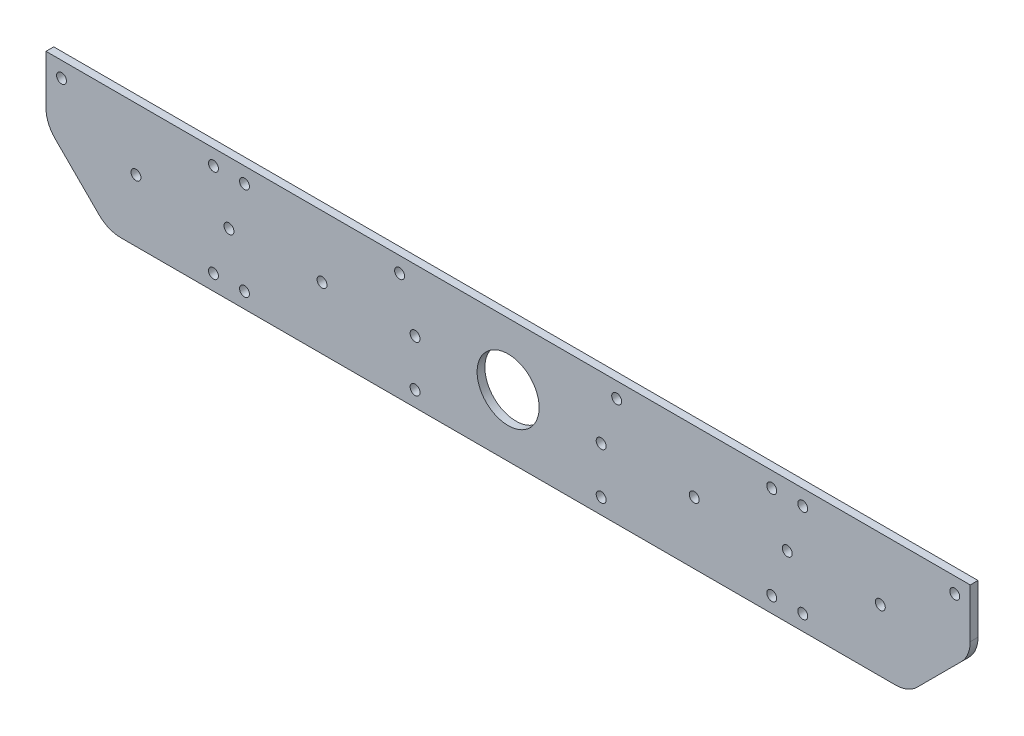
SolidWorks part; units mm, degrees
ref_plane "Front Plane" through (0, 0, 0) normal (0, 0, 1) x (1, 0, 0)
ref_plane "Top Plane" through (0, 0, 0) normal (0, 1, 0) x (1, 0, 0)
ref_plane "Right Plane" through (0, 0, 0) normal (1, 0, 0) x (0, 0, -1)
sketch "Sketch1" plane through (0, 0, 0) normal (0, 0, 1) x (1, 0, 0)
  line L0 (-189.23, 0) -> (189.23, 0) construction
  line L1 (-189.23, -25.4) -> (189.23, -25.4)
  line L2 (-189.23, -25.4) -> (-189.23, 25.4)
  line L3 (-189.23, 25.4) -> (189.23, 25.4)
  line L4 (189.23, -25.4) -> (189.23, 25.4)
  line L5 (0, 25.4) -> (0, -25.4) construction
  circle A0 centre (0, 0) radius 2.032
  circle A9 centre (-38.1, 0) radius 2.032
  circle A10 centre (-76.2, 0) radius 2.032
  circle A11 centre (-114.3, 0) radius 2.032
  circle A12 centre (-152.4, 0) radius 2.032
  circle A13 centre (76.2, 0) radius 2.032
  circle A14 centre (114.3, 0) radius 2.032
  circle A15 centre (152.4, 0) radius 2.032
  circle A16 centre (38.1, 0) radius 2.032
  dimension "D3" = 4.064
  dimension "D5" = 5
  dimension "D1" = 50.8
  dimension "D2" = 378.46
  dimension "D4" = 25.4
  dimension "D6" = 38.1
extrude "Boss-Extrude1" add sketch "Sketch1" along normal blind 3.175
sketch "Sketch2" plane through (0, 0, 3.175) normal (0, 0, 1) x (1, 0, 0)
  circle A0 centre (0, 0) radius 12.7
  dimension "D1" = 25.4
extrude "Cut-Extrude1" cut sketch "Sketch2" against normal through all
sketch "Sketch3" plane through (0, 0, 3.175) normal (0, 0, 1) x (1, 0, 0)
  circle A0 centre (-38.1, -19.05) radius 2.032
  circle A1 centre (-44.45, 19.05) radius 2.032
  circle A2 centre (44.45, 19.05) radius 2.032
  circle A3 centre (38.1, -19.05) radius 2.032
  dimension "D1" = 4.064
extrude "Cut-Extrude2" cut sketch "Sketch3" against normal through all
sketch "Sketch4" plane through (0, 0, 3.175) normal (0, 0, 1) x (1, 0, 0)
  line L0 (-189.23, -25.4) -> (189.23, -25.4) construction
  circle A0 centre (-107.95, -19.05) radius 2.032
  circle A1 centre (-120.65, -19.05) radius 2.032
  circle A2 centre (-120.65, 19.05) radius 2.032
  circle A3 centre (-107.95, 19.05) radius 2.032
  point P2 (-114.3, 0)
  dimension "D1" = 2
  dimension "D6" = 4.064
  dimension "D3" = 6.35
  dimension "D4" = 38.1
  dimension "D5" = 12.7
  dimension "D7" = 6.35
  dimension "D2" = 2
extrude "Cut-Extrude3" cut sketch "Sketch4" against normal through all
sketch "Sketch6" plane through (0, 0, 3.175) normal (0, 0, 1) x (1, 0, 0)
  line L0 (-189.23, 25.4) -> (-189.23, -25.4) construction
  line L1 (-189.23, -25.4) -> (189.23, -25.4) construction
  circle A0 centre (-182.88, 19.05) radius 2.032
  circle A1 centre (-182.88, -19.05) radius 2.032
  dimension "D1" = 38.1
  dimension "D2" = 4.064
  dimension "D3" = 6.35
  dimension "D4" = 6.35
extrude "Cut-Extrude5" cut sketch "Sketch6" against normal through all
mirror "Mirror1" about plane through (0, 0, 0) normal (1, 0, 0) of "Cut-Extrude5", "Cut-Extrude3"
sketch "Sketch7" plane through (0, 0, 3.175) normal (0, 0, 1) x (1, 0, 0)
  line L0 (-189.23, 0) -> (-163.83, -25.4)
  line L1 (-189.23, 25.4) -> (-189.23, -25.4) construction
  line L2 (-189.23, -25.4) -> (189.23, -25.4) construction
  line L3 (-163.83, -25.4) -> (-189.23, -25.4)
  line L4 (-189.23, -25.4) -> (-189.23, 0)
  line L5 (0, 25.4) -> (0, -25.4) construction
  line L6 (189.23, 25.4) -> (-189.23, 25.4) construction
  line L7 (189.23, -25.4) -> (189.23, 0)
  line L8 (163.83, -25.4) -> (189.23, -25.4)
  line L9 (189.23, 0) -> (163.83, -25.4)
  dimension "D1" = 25.4
extrude "Cut-Extrude6" cut sketch "Sketch7" against normal through all
fillet "Fillet1" radius 12.7 4 edges at (189.23, 0, 1.5875) (163.83, -25.4, 1.5875) (-189.23, 0, 1.5875) (-163.83, -25.4, 1.5875)
